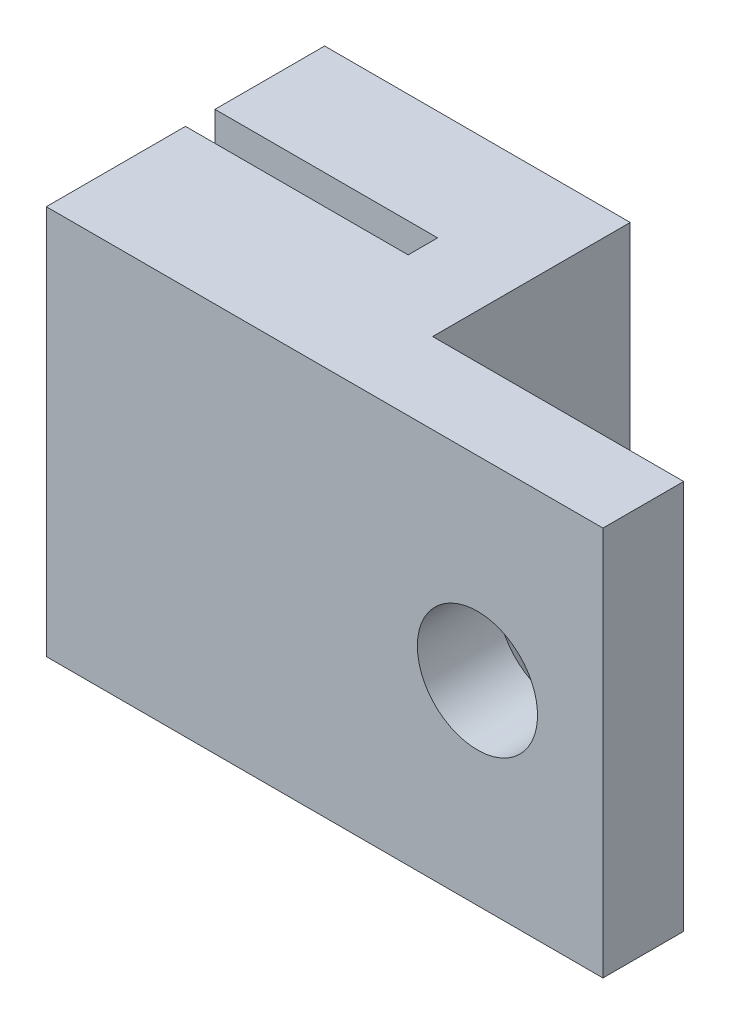
SolidWorks part; units mm, degrees
ref_plane "Front Plane" through (0, 0, 0) normal (0, 0, 1) x (1, 0, 0)
ref_plane "Top Plane" through (0, 0, 0) normal (0, 1, 0) x (1, 0, 0)
ref_plane "Right Plane" through (0, 0, 0) normal (1, 0, 0) x (0, 0, -1)
sketch "Sketch1" plane through (0, 0, 0) normal (0, 1, 0) x (1, 0, 0)
  line L1 (-1237.7101, -397.7364) -> (-1217.7101, -397.7364)
  line L2 (-1237.7101, -397.7364) -> (-1237.7101, -387.7364)
  line L3 (-1237.7101, -387.7364) -> (-1217.7101, -387.7364)
  line L4 (-1217.7101, -397.7364) -> (-1217.7101, -387.7364)
  line L5 (-1237.7101, -391.6764) -> (-1229.7101, -391.6764)
  line L6 (-1237.7101, -391.6764) -> (-1237.7101, -392.7364)
  line L7 (-1237.7101, -392.7364) -> (-1229.7101, -392.7364)
  line L8 (-1229.7101, -391.6764) -> (-1229.7101, -392.7364)
  dimension "D1" = 5
  dimension "D2" = 20
  dimension "D3" = 8
  dimension "D4" = 1.06
  dimension "D5" = 10
extrude "Boss-Extrude1" add sketch "Sketch1" against normal blind 14 contours L5 L8 L7 L2 L1 L4 L3
sketch "Sketch2" plane through (0, 0, 0) normal (0, 1, 0) x (1, 0, 0)
  line L0 (-1237.7101, -387.7364) -> (-1217.7101, -387.7364) construction
  line L1 (-1226.7298, -387.7364) -> (-1217.7101, -387.7364)
  line L2 (-1226.7298, -387.7364) -> (-1226.7298, -394.836)
  line L3 (-1226.7298, -394.836) -> (-1217.7101, -394.836)
  line L4 (-1217.7101, -387.7364) -> (-1217.7101, -394.836)
  line L5 (-1217.7101, -397.7364) -> (-1217.7101, -387.7364) construction
extrude "Cut-Extrude1" cut sketch "Sketch2" against normal through all
sketch "Sketch4" plane through (0, 0, 394.836) normal (0, 0, -1) x (-1, 0, 0)
  line L0 (1226.7298, 0) -> (1217.7101, 0) construction
  line L1 (1222.22, 0) -> (1222.22, -14) construction
  line L2 (1226.7298, -14) -> (1217.7101, -14) construction
  line L3 (1217.7101, -7) -> (1226.7298, -7) construction
  line L4 (1217.7101, -14) -> (1217.7101, 0) construction
  line L5 (1226.7298, -14) -> (1226.7298, 0) construction
  circle A0 centre (1222.22, -7) radius 2.159
  dimension "D1" = 4.318
extrude "Cut-Extrude2" cut sketch "Sketch4" against normal through all
